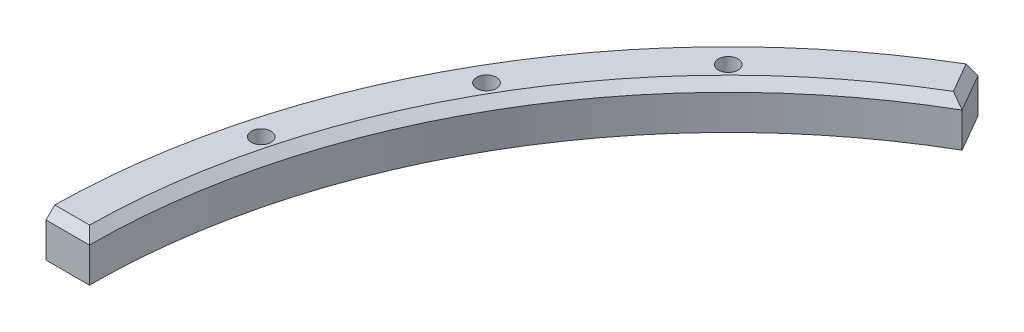
SolidWorks part; units mm, degrees
ref_plane "Front Plane" through (0, 0, 0) normal (0, 0, 1) x (1, 0, 0)
ref_plane "Top Plane" through (0, 0, 0) normal (0, 1, 0) x (1, 0, 0)
ref_plane "Right Plane" through (0, 0, 0) normal (1, 0, 0) x (0, 0, -1)
sketch "Sketch2" plane through (0, 0, 0) normal (0, 1, 0) x (1, 0, 0)
  line L0 (0, 0) -> (-157, 0)
  line L1 (0, 0) -> (-78.5, 135.966)
  circle A0 centre (0, 0) radius 147
  circle A1 centre (0, 0) radius 157
  point P6 (0, 157)
  point P7 (-103.112, 118.3931)
  dimension "D1" = 294
  dimension "D2" = 314
  dimension "D3" = 60
extrude "Boss-Extrude1" add sketch "Sketch2" along normal blind 10 contours L1 A1 L0 A0
sketch "Sketch3" plane through (0, 10, 0) normal (0, 1, 0) x (1, 0, 0)
  line L0 (-157, 0) -> (-147, 0) construction
  line L1 (0, 0) -> (-146.8207, 39.3405) construction
  line L2 (0, 0) -> (-157, 0) construction
  circle A0 centre (0, 0) radius 152 construction
  circle A1 centre (-146.8207, 39.3405) radius 2.25
  point P7 (-152, 0)
  dimension "D1" = 15
  dimension "D2" = 4.5
extrude "Cut-Extrude1" cut sketch "Sketch3" against normal through all
pattern_circular "CirPattern1" count 3 every 15 about axis through (0, 0, 0) along (0, 1, 0) of "Cut-Extrude1"
chamfer "Chamfer1" distance 2 angle 45 3 edges at (-76, 10, -131.6359) (-127.3057, 10, -73.5) (-152, 10, 0)
